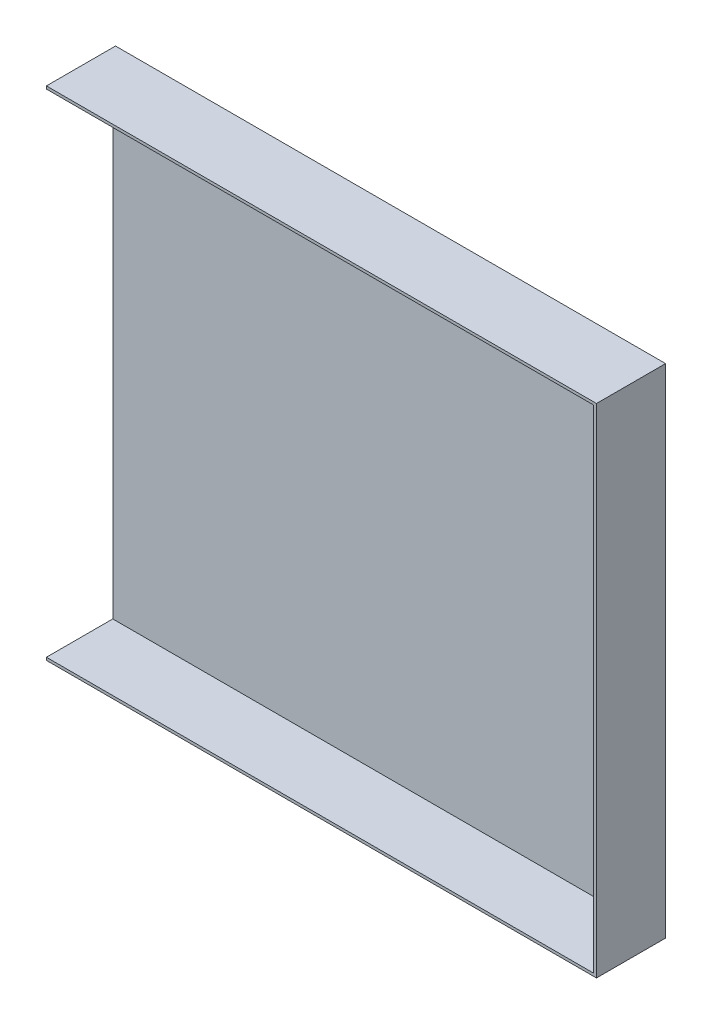
SolidWorks part; units mm, degrees
ref_plane "Plan de face" through (0, 0, 0) normal (0, 0, 1) x (1, 0, 0)
ref_plane "Plan de dessus" through (0, 0, 0) normal (0, 1, 0) x (1, 0, 0)
ref_plane "Plan de droite" through (0, 0, 0) normal (1, 0, 0) x (0, 0, -1)
sketch "Esquisse1" plane through (0, 0, 0) normal (0, 0, 1) x (1, 0, 0)
  line L1 (-200, 180) -> (200, 180)
  line L2 (-200, 180) -> (-200, -180)
  line L3 (-200, -180) -> (200, -180)
  line L4 (200, 180) -> (200, -180)
  line L5 (-200, 180) -> (200, -180) construction
  line L6 (-200, -180) -> (200, 180) construction
  point P0 (0, 0)
  dimension "D1" = 400
  dimension "D2" = 360
extrude "Boss.-Extru.1" add sketch "Esquisse1" along normal blind 50
shell "Coque1" thickness 2
sketch "Esquisse2" plane through (0, 0, 50) normal (0, 0, 1) x (1, 0, 0)
  line L8 (-200, 180) -> (-200, -180) construction
  line L9 (-200, 180) -> (-200, -180)
  line L10 (-198, 178) -> (-198, -178) construction
  line L11 (-198, 180) -> (-198, -180)
  line L12 (-200, 180) -> (-198, 180)
  line L13 (200, 180) -> (-200, 180) construction
  line L14 (-177.2545, -180) -> (-198, -180)
  line L15 (-200, -180) -> (200, -180) construction
extrude "Enlèv. mat.-Extru.2" cut sketch "Esquisse2" against normal blind 50 and the other way through all
